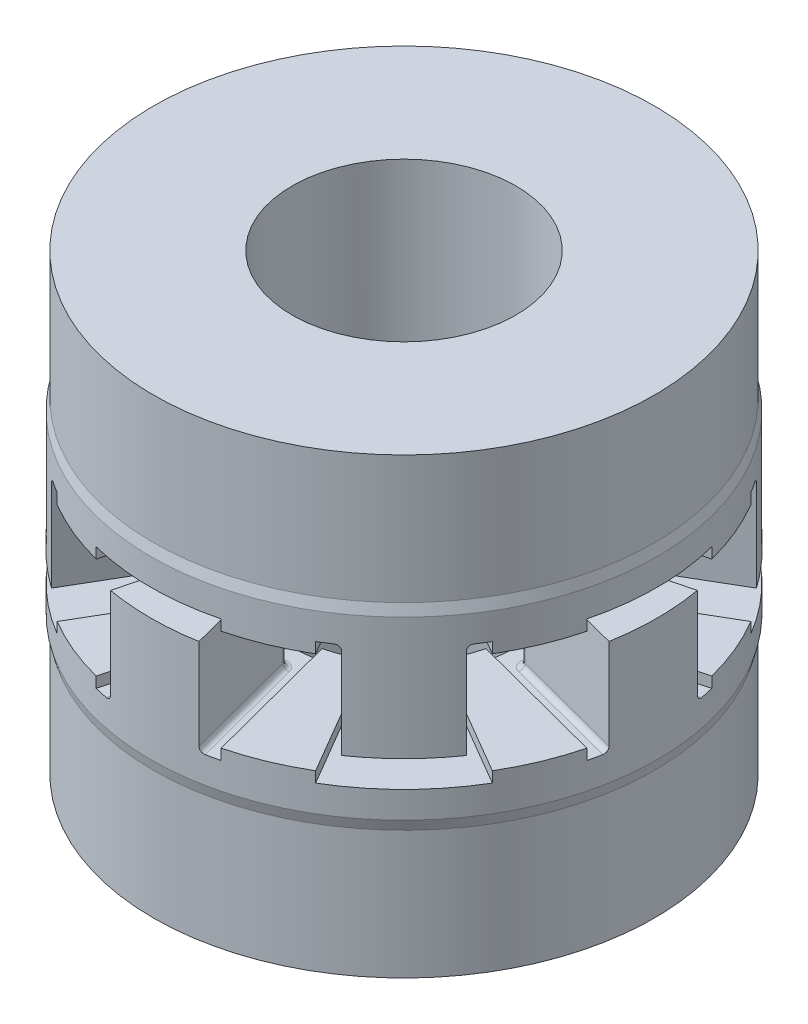
SolidWorks part; units mm, degrees
material "Todos os Aços"
ref_plane "Plano frontal" through (0, 0, 0) normal (0, 0, 1) x (1, 0, 0)
ref_plane "Plano superior" through (0, 0, 0) normal (0, 1, 0) x (1, 0, 0)
ref_plane "Plano direito" through (0, 0, 0) normal (1, 0, 0) x (0, 0, -1)
sketch "Esboço1" plane through (0, 0, 0) normal (0, 0, 1) x (1, 0, 0)
  line L0 (0, 49.0422) -> (0, -43.1916) construction
  line L1 (-21, 0) -> (-47, 0)
  line L2 (-47, 0) -> (-47, 24)
  line L3 (-47, 24) -> (-47.5, 26)
  line L4 (-47.5, 26) -> (-47.5, 49)
  line L5 (-47.5, 49) -> (-21, 49)
  line L6 (-21, 49) -> (-21, 0)
  dimension "D1" = 94
  dimension "D2" = 26
  dimension "D3" = 95
  dimension "D4" = 49
  dimension "D6" = 42
revolve "Revolução1" add sketch "Esboço1" angle 360 about L0
sketch "Esboço2" plane through (0, 49, 0) normal (0, 1, 0) x (1, 0, 0)
  line L0 (-8.3, 46.7692) -> (-2.5, 24.6234)
  line L1 (-46.7692, 8.3) -> (-24.6234, 2.5)
  line L2 (0, 51.6474) -> (0, -59.9036) construction
  line L3 (-57.9771, 0) -> (57.6102, 0) construction
  circle A0 centre (0, 0) radius 47.5 construction
  arc A1 (-2.5, 24.6234) -> (-24.6234, 2.5) centre (0, 0) ccw
  arc A2 (-8.3, 46.7692) -> (-46.7692, 8.3) centre (0, 0) ccw
  dimension "D2" = 24.75
  dimension "D1" = 16.6
  dimension "D3" = 5
  dimension "D4" = 5
  dimension "D5" = 16.6
extrude "Corte-extrusão1" cut sketch "Esboço2" against normal blind 18
pattern_circular "PadrãoCircular1" count 4 over 360 about axis through (0, 0, 0) along (0, 1, 0) of "Corte-extrusão1"
sketch "Esboço3" plane through (0, 49, 0) normal (0, 1, 0) x (1, 0, 0)
  arc A0 (-2.5, 24.6234) -> (-24.6234, 2.5) centre (0, 0) ccw construction
  circle A1 centre (0, 0) radius 24.75
extrude "Corte-extrusão2" cut sketch "Esboço3" against normal up to surface (18 mm away) up to face at (-23.0462, 31, -23.0462)
sketch "Esboço4" plane through (0, 31, 0) normal (0, 1, 0) x (1, 0, 0)
  line L1 (8.3, 46.7692) -> (2.5, 24.6234) construction
  line L2 (-5.8858, 23.7367) -> (-11.6858, 45.8825)
  line L3 (-4.8369, 19.7316) -> (-11.7245, 46.0303)
  line L4 (10.5321, 17.3725) -> (24.2578, 40.8388)
  line L6 (11.7245, 46.0303) -> (4.8369, 19.7316)
  line L7 (40.8388, 24.2578) -> (17.3725, 10.5321)
  line L8 (19.7316, 4.8369) -> (46.0303, 11.7245)
  line L9 (46.0303, -11.7245) -> (19.7316, -4.8369)
  line L10 (17.3725, -10.5321) -> (40.8388, -24.2578)
  line L11 (24.2578, -40.8388) -> (10.5321, -17.3725)
  line L12 (4.8369, -19.7316) -> (11.7245, -46.0303)
  line L13 (-11.7245, -46.0303) -> (-4.8369, -19.7316)
  line L14 (-10.5321, -17.3725) -> (-24.2578, -40.8388)
  line L15 (-40.8388, -24.2578) -> (-17.3725, -10.5321)
  line L16 (-19.7316, -4.8369) -> (-46.0303, -11.7245)
  line L17 (-46.0303, 11.7245) -> (-19.7316, 4.8369)
  line L18 (-17.3725, 10.5321) -> (-40.8388, 24.2578)
  line L19 (-24.2578, 40.8388) -> (-10.5321, 17.3725)
  line L20 (0, 20.9983) -> (0, 0) construction
  arc A0 (4.8369, 19.7316) -> (-4.8369, 19.7316) centre (0, 20.9983) cw
  arc A1 (-11.7245, 46.0303) -> (-24.2578, 40.8388) centre (0, 0) ccw
  arc A3 (24.2578, 40.8388) -> (11.7245, 46.0303) centre (0, 0) ccw
  arc A4 (46.7692, 8.3) -> (8.3, 46.7692) centre (0, 0) ccw construction
  arc A5 (-8.3, 46.7692) -> (-46.7692, 8.3) centre (0, 0) ccw construction
  arc A6 (17.3725, 10.5321) -> (10.5321, 17.3725) centre (14.8481, 14.8481) cw
  arc A7 (19.7316, -4.8369) -> (19.7316, 4.8369) centre (20.9983, 0) cw
  arc A8 (10.5321, -17.3725) -> (17.3725, -10.5321) centre (14.8481, -14.8481) cw
  arc A9 (-4.8369, -19.7316) -> (4.8369, -19.7316) centre (0, -20.9983) cw
  arc A10 (-17.3725, -10.5321) -> (-10.5321, -17.3725) centre (-14.8481, -14.8481) cw
  arc A11 (-19.7316, 4.8369) -> (-19.7316, -4.8369) centre (-20.9983, 0) cw
  arc A12 (-10.5321, 17.3725) -> (-17.3725, 10.5321) centre (-14.8481, 14.8481) cw
  circle A13 centre (0, 0) radius 20.9983 construction
  arc A14 (46.0303, 11.7245) -> (40.8388, 24.2578) centre (0, 0) ccw
  arc A15 (40.8388, -24.2578) -> (46.0303, -11.7245) centre (0, 0) ccw
  arc A16 (11.7245, -46.0303) -> (24.2578, -40.8388) centre (0, 0) ccw
  arc A17 (-24.2578, -40.8388) -> (-11.7245, -46.0303) centre (0, 0) ccw
  arc A18 (-46.0303, -11.7245) -> (-40.8388, -24.2578) centre (0, 0) ccw
  arc A19 (-40.8388, 24.2578) -> (-46.0303, 11.7245) centre (0, 0) ccw
  circle A20 centre (0, 0) radius 21 construction
  circle A21 centre (0, 0) radius 21
  point P53 (0, 0)
  arc M27 (-8.3, 46.7692) -> (-46.7692, 8.3) centre (0, 0) ccw
  arc M31 (-46.7692, -8.3) -> (-8.3, -46.7692) centre (0, 0) ccw
  arc M35 (8.3, -46.7692) -> (46.7692, -8.3) centre (0, 0) ccw
  arc M39 (46.7692, 8.3) -> (8.3, 46.7692) centre (0, 0) ccw
  circle M51 centre (0, 0) radius 21
  dimension "D3" = 5
  dimension "D1" = 3.5
  dimension "D4" = 8
extrude "Ressalto-extrusão1" add sketch "Esboço4" along normal blind 2 contours A11 L16 L15 A10 M51 M31 | A12 L18 L17 A11 M51 M27 | L19 A12 A0 L3 M51 M27 | A6 L4 L6 A0 M51 M39 | A7 L8 L7 A6 M51 M39 | A8 L10 L9 A7 M51 M35 | A9 L12 L11 A8 M51 M35 | A10 L14 L13 A9 M51 M31
fillet "Filete2" radius 1 8 edges at (2.5, 40, 24.6234) (-2.5, 40, 24.6234) (-24.6234, 40, 2.5) (-24.6234, 40, -2.5) (24.6234, 40, 2.5) (24.6234, 40, -2.5) (2.5, 40, -24.6234) (-2.5, 40, -24.6234)
fillet "Filete3" radius 1 20 edges at (-36.1033, 31, -5.5066) (5.5066, 31, 36.1033) (0, 31, 24.75) (-36.1033, 31, 5.5066) (-24.75, 31, 0) (24.75, 31, 0) (36.1033, 31, -5.5066) (0, 31, -24.75) (-5.5066, 31, -36.1033) (2.3296, 31, 24.8789) (-2.3296, 31, 24.8789) (-24.8789, 31, 2.3296) (-24.8789, 31, -2.3296) (24.8789, 31, 2.3296) (24.8789, 31, -2.3296) (2.3296, 31, -24.8789) (-2.3296, 31, -24.8789) (-5.5066, 31, 36.1033) (36.1033, 31, 5.5066) (5.5066, 31, -36.1033)
ref_plane "Plano1" through (0, 42.5, 0) normal (0, -1, 0) x (-1, 0, 0)
mirror "Espelhar1" about plane through (0, 42.5, 0) normal (0, -1, 0) of bodies 105
move or copy body "Corpo-Mover/Copiar1" bodies to move or copy 106 copy no rotation origin (0, 0, 0) rotation axis (0, 1, 0) rotation angle 45
